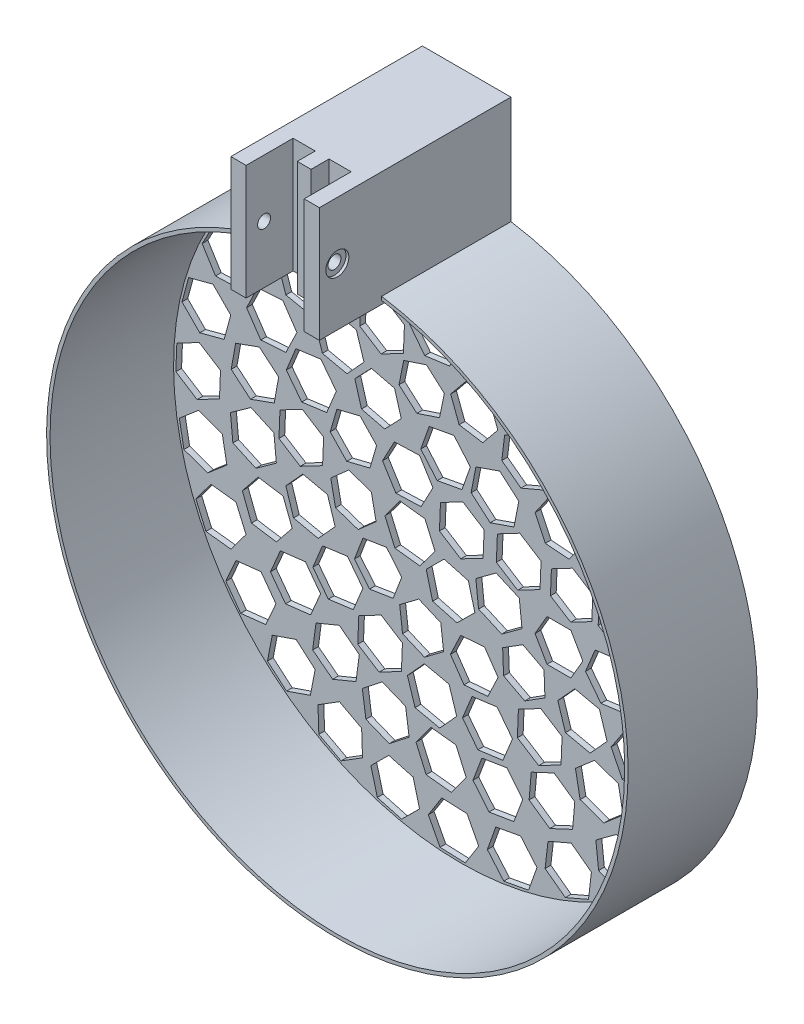
SolidWorks part; units mm, degrees
ref_plane "Plan de face" through (0, 0, 0) normal (0, 0, 1) x (1, 0, 0)
ref_plane "Plan de dessus" through (0, 0, 0) normal (0, 1, 0) x (1, 0, 0)
ref_plane "Plan de droite" through (0, 0, 0) normal (1, 0, 0) x (0, 0, -1)
sketch "Base" plane through (0, 0, 0) normal (0, 1, 0) x (1, 0, 0)
  line L0 (-3.85, -2.4) -> (-3.85, 2.4)
  line L1 (-3.85, 2.4) -> (-10.1, 2.4)
  line L2 (-10.1, 2.4) -> (-10.1, 10.1)
  line L3 (-10.1, 10.1) -> (-2.4, 10.1)
  line L4 (-2.4, 10.1) -> (-2.4, 3.85)
  line L5 (-2.4, 3.85) -> (2.4, 3.85)
  line L6 (0, -55) -> (0, 55) construction
  line L7 (2.4, 10.1) -> (2.4, 3.85)
  line L8 (10.1, 10.1) -> (2.4, 10.1)
  line L9 (10.1, 2.4) -> (10.1, 10.1)
  line L10 (3.85, 2.4) -> (10.1, 2.4)
  line L11 (3.85, -2.4) -> (3.85, 2.4)
  line L12 (-55, 0) -> (55, 0) construction
  line L13 (3.85, -2.4) -> (10.1, -2.4)
  line L14 (10.1, -2.4) -> (10.1, -6.25)
  line L20 (-10.1, -2.4) -> (-10.1, -6.25)
  line L21 (-3.85, -2.4) -> (-10.1, -2.4)
  line L23 (-15.4, 15.4) -> (15.4, 15.4)
  line L24 (-15.4, 15.4) -> (-15.4, -6.25)
  line L26 (15.4, 15.4) -> (15.4, -6.25)
  line L27 (-15.4, 15.4) -> (0, 0) construction
  line L28 (0, 0) -> (15.4, 15.4) construction
  line L29 (-10.1, -6.25) -> (-15.4, -6.25)
  line L30 (10.1, -6.25) -> (15.4, -6.25)
  line L31 (10.1, -10.1) -> (15.4, -15.4) construction
  point P2 (-3.85, 0)
  point P3 (0, 3.85)
  point P27 (0, 0)
  dimension "D1" = 4.8
  dimension "D2" = 4.8
  dimension "D3" = 6.25
  dimension "D4" = 7.7
  dimension "D5" = 30.8
extrude "Boss.-Extru.1" add sketch "Base" along normal mid plane 40
hole_wizard "Chambrage pour vis à six pans creux M41" positions "Esquisse4" profile "Esquisse5" counterbore size "M4" standard "ISO"
sketch "Esquisse4" plane through (15.4, 0, 0) normal (1, 0, 0) x (0, 0, -1)
  point P0 (0, 0)
sketch "Esquisse5" plane through (15.4, 0, 0) normal (0, 1, 0) x (0, 0, -1)
  line L0 (0, 0) -> (0, 11.55)
  line L1 (0, 11.55) -> (2.25, 11.55)
  line L3 (2.25, 11.55) -> (2.25, 1)
  line L4 (2.25, 1) -> (4, 1)
  line L5 (4, 1) -> (4, 0)
  line L7 (4, 0) -> (0, 0)
  line L11 (0, -6.35) -> (0, 107.95) construction
  dimension "Diamètre du perçage jusqu'au prochain" = 4.5
  dimension "Profondeur du perçage jusqu'au prochain" = 11.55
  dimension "Diamètre du chambrage" = 8
  dimension "Profondeur du chambrage" = 1
mirror "Symétrie1" about plane through (0, 0, 0) normal (1, 0, 0) of "Chambrage pour vis à six pans creux M41"
sketch "Esquisse6" plane through (0, 0, 0) normal (0, 0, 1) x (1, 0, 0)
  line L0 (10.1, 20) -> (10.1, -20) construction
  line L1 (-10.1, 20) -> (10.1, 20)
  line L2 (-10.1, 20) -> (-10.1, -20)
  line L3 (-10.1, -20) -> (10.1, -20)
  line L4 (10.1, 20) -> (10.1, -20)
  line L5 (-10.1, 20) -> (10.1, -20) construction
  line L6 (-10.1, -20) -> (10.1, 20) construction
  line L7 (-10.1, 20) -> (-3.85, 20) construction
  point P0 (0, 0)
extrude "Enlèv. mat.-Extru.1" cut sketch "Esquisse6" against normal mid plane 6
sketch "Esquisse16" plane through (0, 0, -15.4) normal (0, 0, -1) x (-1, 0, 0)
  circle A0 centre (0, -117.5665) radius 100
extrude "Extru.-Mince1" add sketch "Esquisse16" along normal blind 45 thin
sketch "Esquisse14" plane through (0, -20, 0) normal (0, -1, 0) x (1, 0, 0)
  line L0 (15.4, 6.25) -> (15.4, -15.4) construction
  line L1 (-15.4, -15.4) -> (15.4, -15.4)
  line L2 (-15.4, -15.4) -> (-15.4, -60.4)
  line L3 (-15.4, -60.4) -> (15.4, -60.4)
  line L4 (15.4, -15.4) -> (15.4, -60.4)
  dimension "D1" = 45
extrude "Boss.-Extru.3" add sketch "Esquisse14" against normal up to vertex (40 mm away)
ref_plane "Plan1" through (15.4, -18.7594, -60.4) normal (0.9881, -0.154, 0) x (0, 0, -1)
sketch "Esquisse17" plane through (0, 0, -60.4) normal (0, 0, -1) x (-1, 0, 0)
  circle A0 centre (0, -117.5665) radius 100
extrude "Boss.-Extru.4" add sketch "Esquisse17" against normal blind 2
sketch "Esquisse18" plane through (0, 0, -60.4) normal (0, 0, -1) x (-1, 0, 0)
  line L0 (-29.3876, -106.503) -> (-25.8265, -98.9869)
  line L1 (-31.1629, -121.4274) -> (-31.5026, -113.1172)
  line L2 (-31.5026, -113.1172) -> (-38.8692, -109.2564)
  line L3 (-38.8692, -109.2564) -> (-45.8961, -113.7056)
  line L4 (-45.8961, -113.7056) -> (-45.5564, -122.0158)
  line L5 (-45.5564, -122.0158) -> (-38.1898, -125.8766)
  line L6 (-38.1898, -125.8766) -> (-31.1629, -121.4274)
  line L7 (-25.8265, -98.9869) -> (-30.5551, -92.1448)
  line L8 (-30.5551, -92.1448) -> (-38.8448, -92.8189)
  line L9 (-38.8448, -92.8189) -> (-42.4059, -100.335)
  line L10 (-42.4059, -100.335) -> (-37.6773, -107.177)
  line L11 (-37.6773, -107.177) -> (-29.3876, -106.503)
  line L12 (-20.88, -94.1131) -> (-14.2339, -89.1129)
  line L13 (-14.2339, -89.1129) -> (-15.2412, -80.8571)
  line L14 (-15.2412, -80.8571) -> (-22.8946, -77.6015)
  line L15 (-22.8946, -77.6015) -> (-29.5407, -82.6018)
  line L16 (-29.5407, -82.6018) -> (-28.5334, -90.8576)
  line L17 (-28.5334, -90.8576) -> (-20.88, -94.1131)
  line L18 (-7.589, -87.0962) -> (0.6196, -85.7573)
  line L19 (0.6196, -85.7573) -> (3.5643, -77.979)
  line L20 (3.5643, -77.979) -> (-1.6995, -71.5396)
  line L21 (-1.6995, -71.5396) -> (-9.908, -72.8785)
  line L22 (-9.908, -72.8785) -> (-12.8528, -80.6568)
  line L23 (-12.8528, -80.6568) -> (-7.589, -87.0962)
  line L24 (7.4406, -87.0596) -> (15.3311, -89.6888)
  line L25 (15.3311, -89.6888) -> (21.5533, -84.1699)
  line L26 (21.5533, -84.1699) -> (19.885, -76.0219)
  line L27 (19.885, -76.0219) -> (11.9944, -73.3928)
  line L28 (11.9944, -73.3928) -> (5.7722, -78.9116)
  line L29 (5.7722, -78.9116) -> (7.4406, -87.0596)
  line L30 (20.7656, -94.0118) -> (26.5304, -100.0067)
  line L31 (26.5304, -100.0067) -> (34.6047, -98.0116)
  line L32 (34.6047, -98.0116) -> (36.914, -90.0216)
  line L33 (36.914, -90.0216) -> (31.1491, -84.0267)
  line L34 (31.1491, -84.0267) -> (23.0749, -86.0218)
  line L35 (23.0749, -86.0218) -> (20.7656, -94.0118)
  line L36 (29.3334, -106.3601) -> (31.652, -114.3474)
  line L37 (31.652, -114.3474) -> (39.7285, -116.3331)
  line L38 (39.7285, -116.3331) -> (45.4864, -110.3315)
  line L39 (45.4864, -110.3315) -> (43.1679, -102.3442)
  line L40 (43.1679, -102.3442) -> (35.0913, -100.3585)
  line L41 (35.0913, -100.3585) -> (29.3334, -106.3601)
  line L42 (31.1813, -121.2756) -> (29.5224, -129.4255)
  line L43 (29.5224, -129.4255) -> (35.751, -134.9371)
  line L44 (35.751, -134.9371) -> (43.6385, -132.2988)
  line L45 (43.6385, -132.2988) -> (45.2974, -124.1489)
  line L46 (45.2974, -124.1489) -> (39.0688, -118.6373)
  line L47 (39.0688, -118.6373) -> (31.1813, -121.2756)
  line L48 (25.886, -135.3414) -> (20.6296, -141.7869)
  line L49 (20.6296, -141.7869) -> (23.5834, -149.5618)
  line L50 (23.5834, -149.5618) -> (31.7935, -150.8912)
  line L51 (31.7935, -150.8912) -> (37.0499, -144.4457)
  line L52 (37.0499, -144.4457) -> (34.0961, -136.6708)
  line L53 (34.0961, -136.6708) -> (25.886, -135.3414)
  line L54 (14.6605, -145.3352) -> (7.0109, -148.5997)
  line L55 (7.0109, -148.5997) -> (6.0131, -156.8567)
  line L56 (6.0131, -156.8567) -> (12.665, -161.8492)
  line L57 (12.665, -161.8492) -> (20.3147, -158.5848)
  line L58 (20.3147, -158.5848) -> (21.3124, -150.3278)
  line L59 (21.3124, -150.3278) -> (14.6605, -145.3352)
  line L60 (0.0764, -148.9676) -> (-8.214, -148.3031)
  line L61 (-8.214, -148.3031) -> (-12.9347, -155.1507)
  line L62 (-12.9347, -155.1507) -> (-9.3649, -162.6626)
  line L63 (-9.3649, -162.6626) -> (-1.0744, -163.3271)
  line L64 (-1.0744, -163.3271) -> (3.6462, -156.4795)
  line L65 (3.6462, -156.4795) -> (0.0764, -148.9676)
  line L66 (-14.5251, -145.4063) -> (-21.5572, -140.9652)
  line L67 (-21.5572, -140.9652) -> (-28.9193, -144.8346)
  line L68 (-28.9193, -144.8346) -> (-29.2494, -153.1451)
  line L69 (-29.2494, -153.1451) -> (-22.2173, -157.5862)
  line L70 (-22.2173, -157.5862) -> (-14.8552, -153.7168)
  line L71 (-14.8552, -153.7168) -> (-14.5251, -145.4063)
  line L72 (-25.7992, -135.4672) -> (-29.9619, -128.2669)
  line L73 (-29.9619, -128.2669) -> (-38.2789, -128.2717)
  line L74 (-38.2789, -128.2717) -> (-42.4332, -135.4769)
  line L75 (-42.4332, -135.4769) -> (-38.2705, -142.6772)
  line L76 (-38.2705, -142.6772) -> (-29.9535, -142.6724)
  line L77 (-29.9535, -142.6724) -> (-25.7992, -135.4672)
  line L78 (-47.7791, -122.0417) -> (-48.1377, -113.2706)
  line L79 (-48.1377, -113.2706) -> (-55.913, -109.1955)
  line L80 (-55.913, -109.1955) -> (-63.3297, -113.8916)
  line L81 (-63.3297, -113.8916) -> (-62.9711, -122.6627)
  line L82 (-62.9711, -122.6627) -> (-55.1958, -126.7378)
  line L83 (-55.1958, -126.7378) -> (-47.7791, -122.0417)
  line L84 (-46.4283, -105.4304) -> (-43.7653, -97.0656)
  line L85 (-43.7653, -97.0656) -> (-49.6779, -90.577)
  line L86 (-49.6779, -90.577) -> (-58.2536, -92.4532)
  line L87 (-58.2536, -92.4532) -> (-60.9165, -100.818)
  line L88 (-60.9165, -100.818) -> (-55.0039, -107.3066)
  line L89 (-55.0039, -107.3066) -> (-46.4283, -105.4304)
  line L90 (-39.4775, -90.2829) -> (-34.1142, -83.3333)
  line L91 (-34.1142, -83.3333) -> (-37.451, -75.2138)
  line L92 (-37.451, -75.2138) -> (-46.1512, -74.0438)
  line L93 (-46.1512, -74.0438) -> (-51.5145, -80.9934)
  line L94 (-51.5145, -80.9934) -> (-48.1777, -89.1129)
  line L95 (-48.1777, -89.1129) -> (-39.4775, -90.2829)
  line L96 (-27.7652, -78.4262) -> (-20.3484, -73.7301)
  line L97 (-20.3484, -73.7301) -> (-20.707, -64.959)
  line L98 (-20.707, -64.959) -> (-28.4823, -60.8839)
  line L99 (-28.4823, -60.8839) -> (-35.899, -65.58)
  line L100 (-35.899, -65.58) -> (-35.5405, -74.3511)
  line L101 (-35.5405, -74.3511) -> (-27.7652, -78.4262)
  line L102 (-12.704, -71.2904) -> (-4.1283, -69.4142)
  line L103 (-4.1283, -69.4142) -> (-1.4654, -61.0494)
  line L104 (-1.4654, -61.0494) -> (-7.378, -54.5608)
  line L105 (-7.378, -54.5608) -> (-15.9536, -56.437)
  line L106 (-15.9536, -56.437) -> (-18.6166, -64.8018)
  line L107 (-18.6166, -64.8018) -> (-12.704, -71.2904)
  line L108 (3.8895, -69.7362) -> (12.5897, -70.9061)
  line L109 (12.5897, -70.9061) -> (17.953, -63.9566)
  line L110 (17.953, -63.9566) -> (14.6162, -55.8371)
  line L111 (14.6162, -55.8371) -> (5.916, -54.6671)
  line L112 (5.916, -54.6671) -> (0.5527, -61.6166)
  line L113 (0.5527, -61.6166) -> (3.8895, -69.7362)
  line L114 (20.0139, -73.951) -> (27.7892, -78.026)
  line L115 (27.7892, -78.026) -> (35.206, -73.3299)
  line L116 (35.206, -73.3299) -> (34.8474, -64.5588)
  line L117 (34.8474, -64.5588) -> (27.0721, -60.4838)
  line L118 (27.0721, -60.4838) -> (19.6554, -65.1799)
  line L119 (19.6554, -65.1799) -> (20.0139, -73.951)
  line L120 (33.7243, -83.4265) -> (39.637, -89.9151)
  line L121 (39.637, -89.9151) -> (48.2126, -88.0389)
  line L122 (48.2126, -88.0389) -> (50.8755, -79.6741)
  line L123 (50.8755, -79.6741) -> (44.9629, -73.1855)
  line L124 (44.9629, -73.1855) -> (36.3873, -75.0617)
  line L125 (36.3873, -75.0617) -> (33.7243, -83.4265)
  line L126 (43.3671, -97.0198) -> (46.7039, -105.1393)
  line L127 (46.7039, -105.1393) -> (55.404, -106.3093)
  line L128 (55.404, -106.3093) -> (60.7673, -99.3597)
  line L129 (60.7673, -99.3597) -> (57.4305, -91.2402)
  line L130 (57.4305, -91.2402) -> (48.7304, -90.0702)
  line L131 (48.7304, -90.0702) -> (43.3671, -97.0198)
  line L132 (47.7791, -113.0913) -> (48.1377, -121.8624)
  line L133 (48.1377, -121.8624) -> (55.913, -125.9375)
  line L134 (55.913, -125.9375) -> (63.3297, -121.2414)
  line L135 (63.3297, -121.2414) -> (62.9711, -112.4703)
  line L136 (62.9711, -112.4703) -> (55.1958, -108.3952)
  line L137 (55.1958, -108.3952) -> (47.7791, -113.0913)
  line L138 (46.4283, -129.7026) -> (43.7653, -138.0674)
  line L139 (43.7653, -138.0674) -> (49.6779, -144.556)
  line L140 (49.6779, -144.556) -> (58.2536, -142.6798)
  line L141 (58.2536, -142.6798) -> (60.9165, -134.315)
  line L142 (60.9165, -134.315) -> (55.0039, -127.8264)
  line L143 (55.0039, -127.8264) -> (46.4283, -129.7026)
  line L144 (39.4775, -144.8501) -> (34.1142, -151.7997)
  line L145 (34.1142, -151.7997) -> (37.451, -159.9192)
  line L146 (37.451, -159.9192) -> (46.1512, -161.0892)
  line L147 (46.1512, -161.0892) -> (51.5145, -154.1396)
  line L148 (51.5145, -154.1396) -> (48.1777, -146.0201)
  line L149 (48.1777, -146.0201) -> (39.4775, -144.8501)
  line L150 (27.7652, -156.7068) -> (20.3484, -161.4029)
  line L151 (20.3484, -161.4029) -> (20.707, -170.174)
  line L152 (20.707, -170.174) -> (28.4823, -174.2491)
  line L153 (28.4823, -174.2491) -> (35.899, -169.553)
  line L154 (35.899, -169.553) -> (35.5405, -160.7819)
  line L155 (35.5405, -160.7819) -> (27.7652, -156.7068)
  line L156 (12.704, -163.8426) -> (4.1283, -165.7188)
  line L157 (4.1283, -165.7188) -> (1.4654, -174.0836)
  line L158 (1.4654, -174.0836) -> (7.378, -180.5722)
  line L159 (7.378, -180.5722) -> (15.9536, -178.696)
  line L160 (15.9536, -178.696) -> (18.6166, -170.3312)
  line L161 (18.6166, -170.3312) -> (12.704, -163.8426)
  line L162 (-3.8895, -165.3968) -> (-12.5897, -164.2269)
  line L163 (-12.5897, -164.2269) -> (-17.953, -171.1764)
  line L164 (-17.953, -171.1764) -> (-14.6162, -179.2959)
  line L165 (-14.6162, -179.2959) -> (-5.916, -180.4659)
  line L166 (-5.916, -180.4659) -> (-0.5527, -173.5164)
  line L167 (-0.5527, -173.5164) -> (-3.8895, -165.3968)
  line L168 (-20.0139, -161.182) -> (-27.7892, -157.107)
  line L169 (-27.7892, -157.107) -> (-35.206, -161.8031)
  line L170 (-35.206, -161.8031) -> (-34.8474, -170.5742)
  line L171 (-34.8474, -170.5742) -> (-27.0721, -174.6492)
  line L172 (-27.0721, -174.6492) -> (-19.6554, -169.9531)
  line L173 (-19.6554, -169.9531) -> (-20.0139, -161.182)
  line L174 (-33.7243, -151.7065) -> (-39.637, -145.2179)
  line L175 (-39.637, -145.2179) -> (-48.2126, -147.0941)
  line L176 (-48.2126, -147.0941) -> (-50.8755, -155.4589)
  line L177 (-50.8755, -155.4589) -> (-44.9629, -161.9475)
  line L178 (-44.9629, -161.9475) -> (-36.3873, -160.0713)
  line L179 (-36.3873, -160.0713) -> (-33.7243, -151.7065)
  line L180 (-43.3671, -138.1132) -> (-46.7039, -129.9937)
  line L181 (-46.7039, -129.9937) -> (-55.404, -128.8237)
  line L182 (-55.404, -128.8237) -> (-60.7673, -135.7733)
  line L183 (-60.7673, -135.7733) -> (-57.4305, -143.8928)
  line L184 (-57.4305, -143.8928) -> (-48.7304, -145.0628)
  line L185 (-48.7304, -145.0628) -> (-43.3671, -138.1132)
  line L186 (-64.853, -123.5923) -> (-65.2116, -114.8211)
  line L187 (-65.2116, -114.8211) -> (-72.9869, -110.7461)
  line L188 (-72.9869, -110.7461) -> (-80.4036, -115.4422)
  line L189 (-80.4036, -115.4422) -> (-80.045, -124.2133)
  line L190 (-80.045, -124.2133) -> (-72.2697, -128.2884)
  line L191 (-72.2697, -128.2884) -> (-64.853, -123.5923)
  line L192 (-64.0738, -105.8717) -> (-62.0526, -97.3291)
  line L193 (-62.0526, -97.3291) -> (-68.4402, -91.3074)
  line L194 (-68.4402, -91.3074) -> (-76.8489, -93.8283)
  line L195 (-76.8489, -93.8283) -> (-78.87, -102.3709)
  line L196 (-72.4825, -108.3926) -> (-64.0738, -105.8717)
  line L197 (-78.87, -102.3709) -> (-72.4825, -108.3926)
  line L198 (-58.5426, -89.0185) -> (-54.2916, -81.3379)
  line L199 (-54.2916, -81.3379) -> (-58.8176, -73.8162)
  line L200 (-58.8176, -73.8162) -> (-67.5946, -73.975)
  line L201 (-67.5946, -73.975) -> (-71.8456, -81.6555)
  line L202 (-67.3196, -89.1773) -> (-58.5426, -89.0185)
  line L203 (-71.8456, -81.6555) -> (-67.3196, -89.1773)
  line L204 (-48.6695, -74.2825) -> (-42.5039, -68.0337)
  line L205 (-42.5039, -68.0337) -> (-44.8328, -59.5698)
  line L206 (-44.8328, -59.5698) -> (-53.3272, -57.3547)
  line L207 (-53.3272, -57.3547) -> (-59.4927, -63.6035)
  line L208 (-57.1639, -72.0674) -> (-48.6695, -74.2825)
  line L209 (-59.4927, -63.6035) -> (-57.1639, -72.0674)
  line L210 (-35.1868, -62.7567) -> (-27.564, -58.4031)
  line L211 (-27.564, -58.4031) -> (-27.523, -49.6247)
  line L212 (-27.523, -49.6247) -> (-35.1047, -45.2)
  line L213 (-35.1047, -45.2) -> (-42.7275, -49.5536)
  line L214 (-42.7686, -58.332) -> (-35.1868, -62.7567)
  line L215 (-42.7275, -49.5536) -> (-42.7686, -58.332)
  line L216 (-19.0945, -55.2959) -> (-10.5797, -53.1603)
  line L217 (-10.5797, -53.1603) -> (-8.1719, -44.7186)
  line L218 (-8.1719, -44.7186) -> (-14.2787, -38.4124)
  line L219 (-14.2787, -38.4124) -> (-22.7934, -40.548)
  line L220 (-25.2013, -48.9898) -> (-19.0945, -55.2959)
  line L221 (-22.7934, -40.548) -> (-25.2013, -48.9898)
  line L222 (-1.586, -52.4535) -> (7.1892, -52.6943)
  line L223 (7.1892, -52.6943) -> (11.7853, -45.2152)
  line L224 (11.7853, -45.2152) -> (7.6063, -37.4953)
  line L225 (7.6063, -37.4953) -> (-1.1688, -37.2545)
  line L226 (-5.765, -44.7335) -> (-1.586, -52.4535)
  line L227 (-1.1688, -37.2545) -> (-5.765, -44.7335)
  line L228 (16.0401, -54.4401) -> (24.4249, -57.0396)
  line L229 (24.4249, -57.0396) -> (30.8684, -51.0778)
  line L230 (30.8684, -51.0778) -> (28.9272, -42.5167)
  line L231 (28.9272, -42.5167) -> (20.5424, -39.9173)
  line L232 (14.0989, -45.879) -> (16.0401, -54.4401)
  line L233 (20.5424, -39.9173) -> (14.0989, -45.879)
  line L234 (32.4766, -61.1086) -> (39.8491, -65.8738)
  line L235 (39.8491, -65.8738) -> (47.6622, -61.8716)
  line L236 (47.6622, -61.8716) -> (48.1027, -53.1042)
  line L237 (48.1027, -53.1042) -> (40.7302, -48.339)
  line L238 (32.9171, -52.3412) -> (32.4766, -61.1086)
  line L239 (40.7302, -48.339) -> (32.9171, -52.3412)
  line L240 (46.5044, -71.9643) -> (52.3179, -78.5419)
  line L241 (52.3179, -78.5419) -> (60.921, -76.796)
  line L242 (60.921, -76.796) -> (63.7106, -68.4726)
  line L243 (63.7106, -68.4726) -> (57.8971, -61.895)
  line L244 (49.294, -63.6409) -> (46.5044, -71.9643)
  line L245 (57.8971, -61.895) -> (49.294, -63.6409)
  line L246 (57.0832, -86.2021) -> (60.9065, -94.1042)
  line L247 (60.9065, -94.1042) -> (69.6616, -94.7442)
  line L248 (69.6616, -94.7442) -> (74.5934, -87.4821)
  line L249 (74.5934, -87.4821) -> (70.7701, -79.5799)
  line L250 (62.015, -78.94) -> (57.0832, -86.2021)
  line L251 (70.7701, -79.5799) -> (62.015, -78.94)
  line L252 (63.4284, -102.766) -> (64.978, -111.4067)
  line L253 (64.978, -111.4067) -> (73.2358, -114.385)
  line L254 (73.2358, -114.385) -> (79.944, -108.7228)
  line L255 (79.944, -108.7228) -> (78.3944, -100.0821)
  line L256 (70.1367, -97.1038) -> (63.4284, -102.766)
  line L257 (78.3944, -100.0821) -> (70.1367, -97.1038)
  line L258 (65.0695, -120.4277) -> (64.2303, -129.1659)
  line L259 (64.2303, -129.1659) -> (71.3783, -134.2618)
  line L260 (71.3783, -134.2618) -> (79.3655, -130.6193)
  line L261 (79.3655, -130.6193) -> (80.2046, -121.8811)
  line L262 (73.0566, -116.7852) -> (65.0695, -120.4277)
  line L263 (80.2046, -121.8811) -> (73.0566, -116.7852)
  line L264 (61.8846, -137.8771) -> (58.719, -146.0649)
  line L265 (58.719, -146.0649) -> (64.2271, -152.9003)
  line L266 (64.2271, -152.9003) -> (72.9008, -151.5478)
  line L267 (72.9008, -151.5478) -> (76.0663, -143.36)
  line L268 (70.5582, -136.5246) -> (61.8846, -137.8771)
  line L269 (76.0663, -143.36) -> (70.5582, -136.5246)
  line L270 (54.11, -153.8202) -> (48.8528, -160.8503)
  line L271 (48.8528, -160.8503) -> (52.3125, -168.9183)
  line L272 (52.3125, -168.9183) -> (61.0293, -169.9561)
  line L273 (61.0293, -169.9561) -> (66.2866, -162.926)
  line L274 (62.8269, -154.858) -> (54.11, -153.8202)
  line L275 (66.2866, -162.926) -> (62.8269, -154.858)
  line L276 (42.3223, -167.0745) -> (35.3633, -172.4256)
  line L277 (35.3633, -172.4256) -> (36.518, -181.1278)
  line L278 (36.518, -181.1278) -> (44.6317, -184.4789)
  line L279 (44.6317, -184.4789) -> (51.5906, -179.1278)
  line L280 (50.436, -170.4256) -> (42.3223, -167.0745)
  line L281 (51.5906, -179.1278) -> (50.436, -170.4256)
  line L282 (27.3958, -176.657) -> (19.2512, -179.9322)
  line L283 (19.2512, -179.9322) -> (18.0152, -188.6232)
  line L284 (18.0152, -188.6232) -> (24.9239, -194.0391)
  line L285 (24.9239, -194.0391) -> (33.0685, -190.7639)
  line L286 (34.3044, -182.0729) -> (27.3958, -176.657)
  line L287 (33.0685, -190.7639) -> (34.3044, -182.0729)
  line L288 (10.4374, -181.8571) -> (1.7112, -182.8134)
  line L289 (1.7112, -182.8134) -> (-1.8237, -190.8487)
  line L290 (-1.8237, -190.8487) -> (3.3676, -197.9276)
  line L291 (3.3676, -197.9276) -> (12.0938, -196.9714)
  line L292 (15.6287, -188.9361) -> (10.4374, -181.8571)
  line L293 (12.0938, -196.9714) -> (15.6287, -188.9361)
  line L294 (-7.295, -182.289) -> (-15.9556, -180.8555)
  line L295 (-15.9556, -180.8555) -> (-21.5274, -187.6391)
  line L296 (-21.5274, -187.6391) -> (-18.4385, -195.8562)
  line L297 (-18.4385, -195.8562) -> (-9.7779, -197.2897)
  line L298 (-4.2061, -190.5061) -> (-7.295, -182.289)
  line L299 (-9.7779, -197.2897) -> (-4.2061, -190.5061)
  line L300 (-24.4864, -177.9208) -> (-32.4391, -174.2038)
  line L301 (-32.4391, -174.2038) -> (-39.6344, -179.2326)
  line L302 (-39.6344, -179.2326) -> (-38.877, -187.9783)
  line L303 (-38.877, -187.9783) -> (-30.9243, -191.6953)
  line L304 (-23.729, -186.6665) -> (-24.4864, -177.9208)
  line L305 (-30.9243, -191.6953) -> (-23.729, -186.6665)
  line L306 (-39.8618, -169.0763) -> (-46.5168, -163.3516)
  line L307 (-46.5168, -163.3516) -> (-54.802, -166.2526)
  line L308 (-54.802, -166.2526) -> (-56.4323, -174.8784)
  line L309 (-56.4323, -174.8784) -> (-49.7773, -180.6031)
  line L310 (-41.492, -177.7021) -> (-39.8618, -169.0763)
  line L311 (-49.7773, -180.6031) -> (-41.492, -177.7021)
  line L312 (-52.2808, -156.4116) -> (-57.1445, -149.1037)
  line L313 (-57.1445, -149.1037) -> (-65.9052, -149.6618)
  line L314 (-65.9052, -149.6618) -> (-69.8022, -157.5279)
  line L315 (-69.8022, -157.5279) -> (-64.9385, -164.8358)
  line L316 (-56.1778, -164.2777) -> (-52.2808, -156.4116)
  line L317 (-64.9385, -164.8358) -> (-56.1778, -164.2777)
  line L318 (-60.8223, -140.8659) -> (-63.534, -132.5168)
  line L319 (-63.534, -132.5168) -> (-72.1204, -130.6906)
  line L320 (-72.1204, -130.6906) -> (-77.9952, -137.2136)
  line L321 (-77.9952, -137.2136) -> (-75.2835, -145.5627)
  line L322 (-66.6971, -147.3889) -> (-60.8223, -140.8659)
  line L323 (-75.2835, -145.5627) -> (-66.6971, -147.3889)
  line L324 (-12.3377, -120.7572) -> (-12.6963, -111.9861)
  line L325 (-12.6963, -111.9861) -> (-20.4716, -107.911)
  line L326 (-20.4716, -107.911) -> (-27.8883, -112.6071)
  line L327 (-27.8883, -112.6071) -> (-27.5298, -121.3783)
  line L328 (-27.5298, -121.3783) -> (-19.7545, -125.4533)
  line L329 (-19.7545, -125.4533) -> (-12.3377, -120.7572)
  line L330 (-10.1871, -109.9098) -> (-3.5531, -104.1608)
  line L331 (-3.5531, -104.1608) -> (-5.2149, -95.5411)
  line L332 (-5.2149, -95.5411) -> (-13.5107, -92.6704)
  line L333 (-20.1447, -98.4194) -> (-18.4829, -107.0392)
  line L334 (-18.4829, -107.0392) -> (-10.1871, -109.9098)
  line L335 (-13.5107, -92.6704) -> (-20.1447, -98.4194)
  line L336 (-0.3653, -104.8281) -> (8.2657, -106.4303)
  line L337 (8.2657, -106.4303) -> (13.9687, -99.7567)
  line L338 (13.9687, -99.7567) -> (11.0408, -91.4809)
  line L339 (2.4098, -89.8788) -> (-3.2933, -96.5523)
  line L340 (-3.2933, -96.5523) -> (-0.3653, -104.8281)
  line L341 (11.0408, -91.4809) -> (2.4098, -89.8788)
  line L342 (9.7315, -109.3386) -> (13.8602, -117.0856)
  line L343 (13.8602, -117.0856) -> (22.6336, -117.3835)
  line L344 (22.6336, -117.3835) -> (27.2783, -109.9344)
  line L345 (23.1496, -102.1875) -> (14.3762, -101.8896)
  line L346 (14.3762, -101.8896) -> (9.7315, -109.3386)
  line L347 (27.2783, -109.9344) -> (23.1496, -102.1875)
  line L348 (12.5003, -120.0449) -> (9.0177, -128.103)
  line L349 (9.0177, -128.103) -> (14.2549, -135.1481)
  line L350 (14.2549, -135.1481) -> (22.9747, -134.135)
  line L351 (26.4573, -126.077) -> (21.2201, -119.0319)
  line L352 (21.2201, -119.0319) -> (12.5003, -120.0449)
  line L353 (22.9747, -134.135) -> (26.4573, -126.077)
  line L354 (5.8561, -128.8849) -> (-2.6153, -131.1862)
  line L355 (-2.6153, -131.1862) -> (-4.858, -139.6734)
  line L356 (-4.858, -139.6734) -> (1.3707, -145.8592)
  line L357 (9.8421, -143.5579) -> (12.0848, -135.0707)
  line L358 (12.0848, -135.0707) -> (5.8561, -128.8849)
  line L359 (1.3707, -145.8592) -> (9.8421, -143.5579)
  line L360 (-5.1979, -129.2019) -> (-12.279, -124.0135)
  line L361 (-12.279, -124.0135) -> (-20.3128, -127.5518)
  line L362 (-20.3128, -127.5518) -> (-21.2655, -136.2784)
  line L363 (-14.1844, -141.4667) -> (-6.1506, -137.9285)
  line L364 (-6.1506, -137.9285) -> (-5.1979, -129.2019)
  line L365 (-21.2655, -136.2784) -> (-14.1844, -141.4667)
  line L366 (-83.6712, -124.2141) -> (-84.0298, -115.443)
  line L367 (-84.0298, -115.443) -> (-91.8051, -111.3679)
  line L368 (-91.8051, -111.3679) -> (-99.2218, -116.064)
  line L369 (-99.2218, -116.064) -> (-98.8633, -124.8351)
  line L370 (-98.8633, -124.8351) -> (-91.088, -128.9102)
  line L371 (-91.088, -128.9102) -> (-83.6712, -124.2141)
  line L372 (7.4712, -121.2135) -> (7.1126, -112.4423)
  line L373 (7.1126, -112.4423) -> (-0.6627, -108.3673)
  line L374 (-0.6627, -108.3673) -> (-8.0794, -113.0634)
  line L375 (-8.0794, -113.0634) -> (-7.7209, -121.8345)
  line L376 (-7.7209, -121.8345) -> (0.0544, -125.9096)
  line L377 (0.0544, -125.9096) -> (7.4712, -121.2135)
  line L378 (-83.0526, -105.4288) -> (-81.4504, -96.7978)
  line L379 (-81.4504, -96.7978) -> (-88.124, -91.0948)
  line L380 (-88.124, -91.0948) -> (-96.3998, -94.0227)
  line L381 (-96.3998, -94.0227) -> (-98.002, -102.6537)
  line L382 (-98.002, -102.6537) -> (-91.3284, -108.3568)
  line L383 (-91.3284, -108.3568) -> (-83.0526, -105.4288)
  line L384 (-78.2694, -87.2522) -> (-74.7868, -79.1941)
  line L385 (-74.7868, -79.1941) -> (-80.024, -72.149)
  line L386 (-80.024, -72.149) -> (-88.7439, -73.1621)
  line L387 (-88.7439, -73.1621) -> (-92.2265, -81.2202)
  line L388 (-92.2265, -81.2202) -> (-86.9893, -88.2652)
  line L389 (-86.9893, -88.2652) -> (-78.2694, -87.2522)
  line L390 (-69.5615, -70.5956) -> (-64.3731, -63.5145)
  line L391 (-64.3731, -63.5145) -> (-67.9113, -55.4807)
  line L392 (-67.9113, -55.4807) -> (-76.6379, -54.528)
  line L393 (-76.6379, -54.528) -> (-81.8263, -61.6091)
  line L394 (-81.8263, -61.6091) -> (-78.2881, -69.6429)
  line L395 (-78.2881, -69.6429) -> (-69.5615, -70.5956)
  line L396 (-57.3654, -56.2944) -> (-50.7315, -50.5454)
  line L397 (-50.7315, -50.5454) -> (-52.3933, -41.9256)
  line L398 (-52.3933, -41.9256) -> (-60.6891, -39.055)
  line L399 (-60.6891, -39.055) -> (-67.3231, -44.804)
  line L400 (-67.3231, -44.804) -> (-65.6613, -53.4237)
  line L401 (-65.6613, -53.4237) -> (-57.3654, -56.2944)
  line L402 (-42.2929, -45.0656) -> (-34.5459, -40.9369)
  line L403 (-34.5459, -40.9369) -> (-34.248, -32.1635)
  line L404 (-34.248, -32.1635) -> (-41.697, -27.5188)
  line L405 (-41.697, -27.5188) -> (-49.444, -31.6475)
  line L406 (-49.444, -31.6475) -> (-49.7419, -40.4209)
  line L407 (-49.7419, -40.4209) -> (-42.2929, -45.0656)
  line L408 (-25.0995, -37.4723) -> (-16.6281, -35.171)
  line L409 (-16.6281, -35.171) -> (-14.3854, -26.6839)
  line L410 (-14.3854, -26.6839) -> (-20.6141, -20.498)
  line L411 (-20.6141, -20.498) -> (-29.0855, -22.7994)
  line L412 (-29.0855, -22.7994) -> (-31.3282, -31.2865)
  line L413 (-31.3282, -31.2865) -> (-25.0995, -37.4723)
  line L414 (-6.6476, -33.8953) -> (2.1235, -33.5367)
  line L415 (2.1235, -33.5367) -> (6.1986, -25.7614)
  line L416 (6.1986, -25.7614) -> (1.5025, -18.3447)
  line L417 (1.5025, -18.3447) -> (-7.2686, -18.7032)
  line L418 (-7.2686, -18.7032) -> (-11.3437, -26.4785)
  line L419 (-11.3437, -26.4785) -> (-6.6476, -33.8953)
  line L420 (12.1377, -34.5139) -> (20.7687, -36.1161)
  line L421 (20.7687, -36.1161) -> (26.4717, -29.4425)
  line L422 (26.4717, -29.4425) -> (23.5438, -21.1667)
  line L423 (23.5438, -21.1667) -> (14.9128, -19.5645)
  line L424 (14.9128, -19.5645) -> (9.2097, -26.2381)
  line L425 (9.2097, -26.2381) -> (12.1377, -34.5139)
  line L426 (30.3143, -39.2971) -> (38.3724, -42.7797)
  line L427 (38.3724, -42.7797) -> (45.4175, -37.5425)
  line L428 (45.4175, -37.5425) -> (44.4044, -28.8226)
  line L429 (44.4044, -28.8226) -> (36.3464, -25.34)
  line L430 (36.3464, -25.34) -> (29.3013, -30.5772)
  line L431 (29.3013, -30.5772) -> (30.3143, -39.2971)
  line L432 (46.9709, -48.005) -> (54.052, -53.1934)
  line L433 (54.052, -53.1934) -> (62.0858, -49.6552)
  line L434 (62.0858, -49.6552) -> (63.0385, -40.9286)
  line L435 (63.0385, -40.9286) -> (55.9574, -35.7402)
  line L436 (55.9574, -35.7402) -> (47.9236, -39.2784)
  line L437 (47.9236, -39.2784) -> (46.9709, -48.005)
  line L438 (61.2721, -60.2011) -> (67.0211, -66.835)
  line L439 (67.0211, -66.835) -> (75.6409, -65.1732)
  line L440 (75.6409, -65.1732) -> (78.5115, -56.8774)
  line L441 (78.5115, -56.8774) -> (72.7625, -50.2434)
  line L442 (72.7625, -50.2434) -> (64.1428, -51.9052)
  line L443 (64.1428, -51.9052) -> (61.2721, -60.2011)
  line L444 (72.5009, -75.2736) -> (76.6296, -83.0206)
  line L445 (76.6296, -83.0206) -> (85.403, -83.3185)
  line L446 (85.403, -83.3185) -> (90.0477, -75.8695)
  line L447 (90.0477, -75.8695) -> (85.919, -68.1225)
  line L448 (85.919, -68.1225) -> (77.1456, -67.8246)
  line L449 (77.1456, -67.8246) -> (72.5009, -75.2736)
  line L450 (80.0942, -92.467) -> (82.3955, -100.9384)
  line L451 (82.3955, -100.9384) -> (90.8826, -103.1811)
  line L452 (90.8826, -103.1811) -> (97.0685, -96.9524)
  line L453 (97.0685, -96.9524) -> (94.7671, -88.481)
  line L454 (94.7671, -88.481) -> (86.28, -86.2383)
  line L455 (86.28, -86.2383) -> (80.0942, -92.467)
  line L456 (83.6712, -110.9189) -> (84.0298, -119.69)
  line L457 (84.0298, -119.69) -> (91.8051, -123.7651)
  line L458 (91.8051, -123.7651) -> (99.2218, -119.069)
  line L459 (99.2218, -119.069) -> (98.8633, -110.2979)
  line L460 (98.8633, -110.2979) -> (91.088, -106.2228)
  line L461 (91.088, -106.2228) -> (83.6712, -110.9189)
  line L462 (83.0526, -129.7042) -> (81.4504, -138.3352)
  line L463 (81.4504, -138.3352) -> (88.124, -144.0382)
  line L464 (88.124, -144.0382) -> (96.3998, -141.1103)
  line L465 (96.3998, -141.1103) -> (98.002, -132.4793)
  line L466 (98.002, -132.4793) -> (91.3284, -126.7762)
  line L467 (91.3284, -126.7762) -> (83.0526, -129.7042)
  line L468 (78.2694, -147.8808) -> (74.7868, -155.9389)
  line L469 (74.7868, -155.9389) -> (80.024, -162.984)
  line L470 (80.024, -162.984) -> (88.7439, -161.9709)
  line L471 (88.7439, -161.9709) -> (92.2265, -153.9129)
  line L472 (92.2265, -153.9129) -> (86.9893, -146.8678)
  line L473 (86.9893, -146.8678) -> (78.2694, -147.8808)
  line L474 (69.5615, -164.5374) -> (64.3731, -171.6185)
  line L475 (64.3731, -171.6185) -> (67.9113, -179.6523)
  line L476 (67.9113, -179.6523) -> (76.6379, -180.605)
  line L477 (76.6379, -180.605) -> (81.8263, -173.5239)
  line L478 (81.8263, -173.5239) -> (78.2881, -165.4901)
  line L479 (78.2881, -165.4901) -> (69.5615, -164.5374)
  line L480 (57.3654, -178.8386) -> (50.7315, -184.5876)
  line L481 (50.7315, -184.5876) -> (52.3933, -193.2074)
  line L482 (52.3933, -193.2074) -> (60.6891, -196.078)
  line L483 (60.6891, -196.078) -> (67.3231, -190.329)
  line L484 (67.3231, -190.329) -> (65.6613, -181.7093)
  line L485 (65.6613, -181.7093) -> (57.3654, -178.8386)
  line L486 (42.2929, -190.0674) -> (34.5459, -194.1961)
  line L487 (34.5459, -194.1961) -> (34.248, -202.9695)
  line L488 (34.248, -202.9695) -> (41.697, -207.6142)
  line L489 (41.697, -207.6142) -> (49.444, -203.4855)
  line L490 (49.444, -203.4855) -> (49.7419, -194.7121)
  line L491 (49.7419, -194.7121) -> (42.2929, -190.0674)
  line L492 (25.0995, -197.6607) -> (16.6281, -199.962)
  line L493 (16.6281, -199.962) -> (14.3854, -208.4491)
  line L494 (14.3854, -208.4491) -> (20.6141, -214.635)
  line L495 (20.6141, -214.635) -> (29.0855, -212.3336)
  line L496 (29.0855, -212.3336) -> (31.3282, -203.8465)
  line L497 (31.3282, -203.8465) -> (25.0995, -197.6607)
  line L498 (6.6476, -201.2377) -> (-2.1235, -201.5963)
  line L499 (-2.1235, -201.5963) -> (-6.1986, -209.3716)
  line L500 (-6.1986, -209.3716) -> (-1.5025, -216.7883)
  line L501 (-1.5025, -216.7883) -> (7.2686, -216.4298)
  line L502 (7.2686, -216.4298) -> (11.3437, -208.6545)
  line L503 (11.3437, -208.6545) -> (6.6476, -201.2377)
  line L504 (-12.1377, -200.6191) -> (-20.7687, -199.0169)
  line L505 (-20.7687, -199.0169) -> (-26.4717, -205.6905)
  line L506 (-26.4717, -205.6905) -> (-23.5438, -213.9663)
  line L507 (-23.5438, -213.9663) -> (-14.9128, -215.5685)
  line L508 (-14.9128, -215.5685) -> (-9.2097, -208.8949)
  line L509 (-9.2097, -208.8949) -> (-12.1377, -200.6191)
  line L510 (-30.3143, -195.8359) -> (-38.3724, -192.3533)
  line L511 (-38.3724, -192.3533) -> (-45.4175, -197.5905)
  line L512 (-45.4175, -197.5905) -> (-44.4044, -206.3104)
  line L513 (-44.4044, -206.3104) -> (-36.3464, -209.793)
  line L514 (-36.3464, -209.793) -> (-29.3013, -204.5558)
  line L515 (-29.3013, -204.5558) -> (-30.3143, -195.8359)
  line L516 (-46.9709, -187.128) -> (-54.052, -181.9396)
  line L517 (-54.052, -181.9396) -> (-62.0858, -185.4778)
  line L518 (-62.0858, -185.4778) -> (-63.0385, -194.2044)
  line L519 (-63.0385, -194.2044) -> (-55.9574, -199.3928)
  line L520 (-55.9574, -199.3928) -> (-47.9236, -195.8546)
  line L521 (-47.9236, -195.8546) -> (-46.9709, -187.128)
  line L522 (-61.2721, -174.9319) -> (-67.0211, -168.298)
  line L523 (-67.0211, -168.298) -> (-75.6409, -169.9598)
  line L524 (-75.6409, -169.9598) -> (-78.5115, -178.2556)
  line L525 (-78.5115, -178.2556) -> (-72.7625, -184.8896)
  line L526 (-72.7625, -184.8896) -> (-64.1428, -183.2278)
  line L527 (-64.1428, -183.2278) -> (-61.2721, -174.9319)
  line L528 (-72.5009, -159.8594) -> (-76.6296, -152.1124)
  line L529 (-76.6296, -152.1124) -> (-85.403, -151.8145)
  line L530 (-85.403, -151.8145) -> (-90.0477, -159.2635)
  line L531 (-90.0477, -159.2635) -> (-85.919, -167.0105)
  line L532 (-85.919, -167.0105) -> (-77.1456, -167.3084)
  line L533 (-77.1456, -167.3084) -> (-72.5009, -159.8594)
  line L534 (-80.0942, -142.666) -> (-82.3955, -134.1946)
  line L535 (-82.3955, -134.1946) -> (-90.8826, -131.9519)
  line L536 (-90.8826, -131.9519) -> (-97.0685, -138.1806)
  line L537 (-97.0685, -138.1806) -> (-94.7671, -146.652)
  line L538 (-94.7671, -146.652) -> (-86.28, -148.8947)
  line L539 (-86.28, -148.8947) -> (-80.0942, -142.666)
  circle A0 centre (0, -117.5665) radius 38.5295 construction
  circle A1 centre (0, -117.5665) radius 60 construction
  circle A2 centre (0, -117.5665) radius 85 construction
  circle A3 centre (-38.5295, -117.5665) radius 7.2028 construction
  point P88 (0, -117.5665)
  point P197 (0, -117.5665)
  point P336 (0, -117.5665)
  point P379 (0, -117.5665)
  point P554 (0, -117.5665)
  dimension "D1" = 13
  dimension "D2" = 18
  dimension "D3" = 23
  dimension "D4" = 7
  dimension "D5" = 28
extrude "Enlèv. mat.-Extru.2" cut sketch "Esquisse18" against normal blind 2
